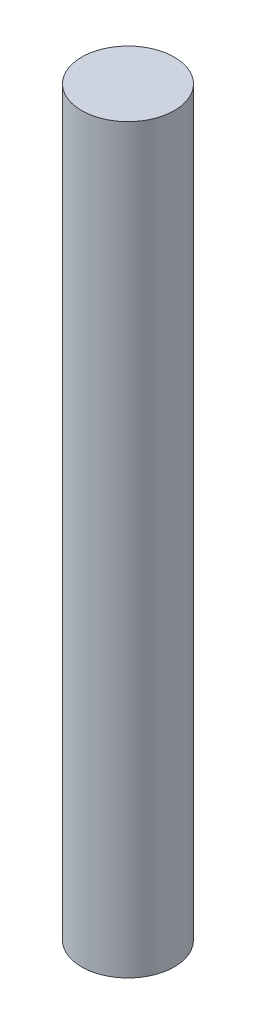
SolidWorks part; units mm, degrees
material "镀铬不锈钢"
ref_plane "前视基准面" through (0, 0, 0) normal (0, 0, 1) x (1, 0, 0)
ref_plane "上视基准面" through (0, 0, 0) normal (0, 1, 0) x (1, 0, 0)
ref_plane "右视基准面" through (0, 0, 0) normal (1, 0, 0) x (0, 0, -1)
sketch "草图1" plane through (0, 0, 0) normal (0, 1, 0) x (1, 0, 0)
  circle A0 centre (0, 0) radius 2.5
  dimension "D1" = 5
extrude "凸台-拉伸1" add sketch "草图1" along normal blind 40
